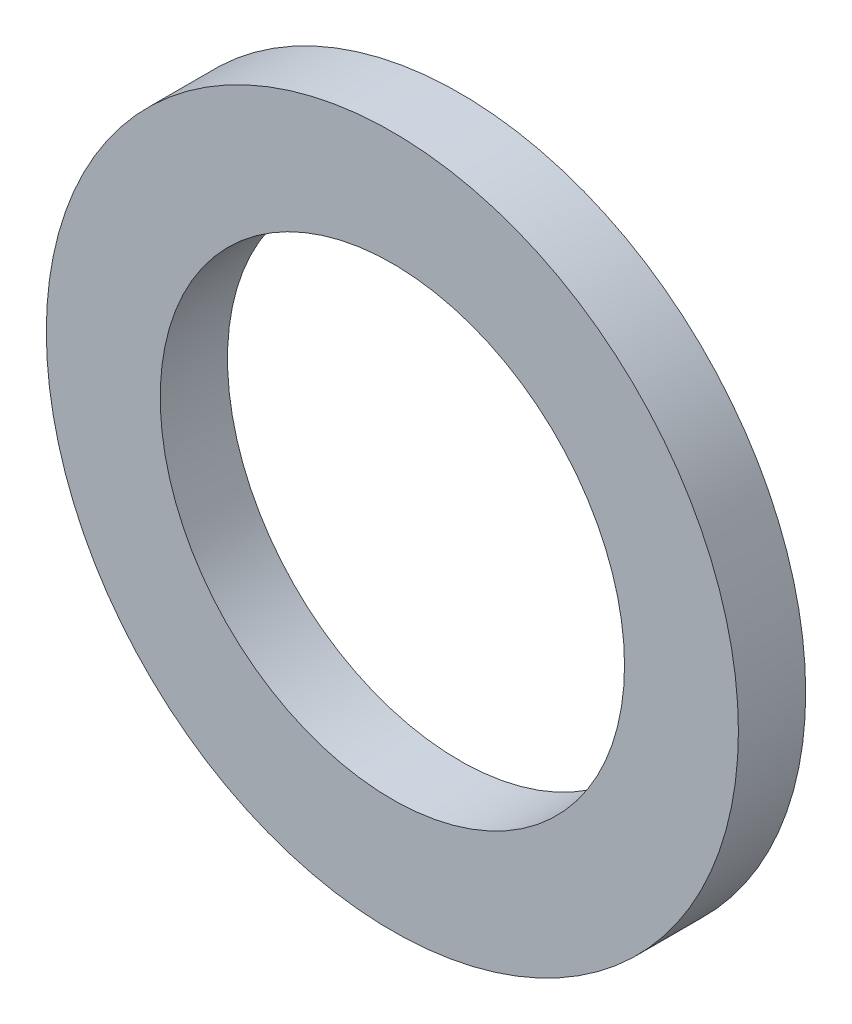
SolidWorks part; units mm, degrees
ref_plane "Ön Düzlem" through (0, 0, 0) normal (0, 0, 1) x (1, 0, 0)
ref_plane "Üst Düzlem" through (0, 0, 0) normal (0, 1, 0) x (1, 0, 0)
ref_plane "Sağ Düzlem" through (0, 0, 0) normal (1, 0, 0) x (0, 0, -1)
sketch "Çizim1" plane through (0, 0, 0) normal (0, 0, 1) x (1, 0, 0)
  circle A0 centre (0, 0) radius 10.285
  circle A1 centre (0, 0) radius 6.9
  dimension "D1" = 20.57
  dimension "D2" = 13.8
extrude "Yükseklik-Ekstrüzyon1" add sketch "Çizim1" along normal blind 2
